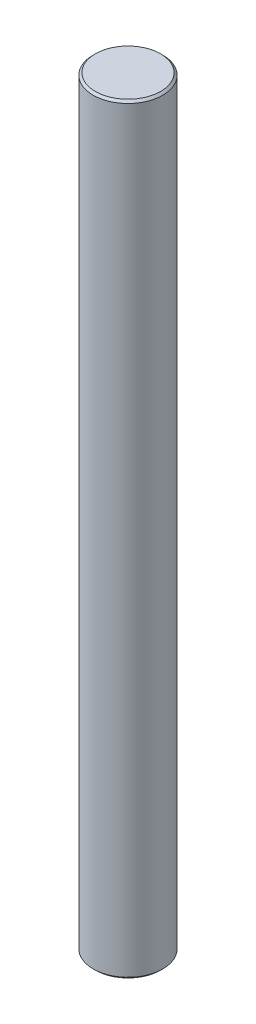
SolidWorks part; units mm, degrees
ref_plane "前视基准面" through (0, 0, 0) normal (0, 0, 1) x (1, 0, 0)
ref_plane "上视基准面" through (0, 0, 0) normal (0, 1, 0) x (1, 0, 0)
ref_plane "右视基准面" through (0, 0, 0) normal (1, 0, 0) x (0, 0, -1)
sketch "草图1" plane through (0, 0, 0) normal (0, 1, 0) x (1, 0, 0)
  circle A0 centre (0, 0) radius 16
  dimension "D1" = 32
extrude "凸台-拉伸1" add sketch "草图1" along normal blind 350
chamfer "倒角1" distance 1 angle 45 2 edges at (0, 0, 16) (0, 350, 16)
